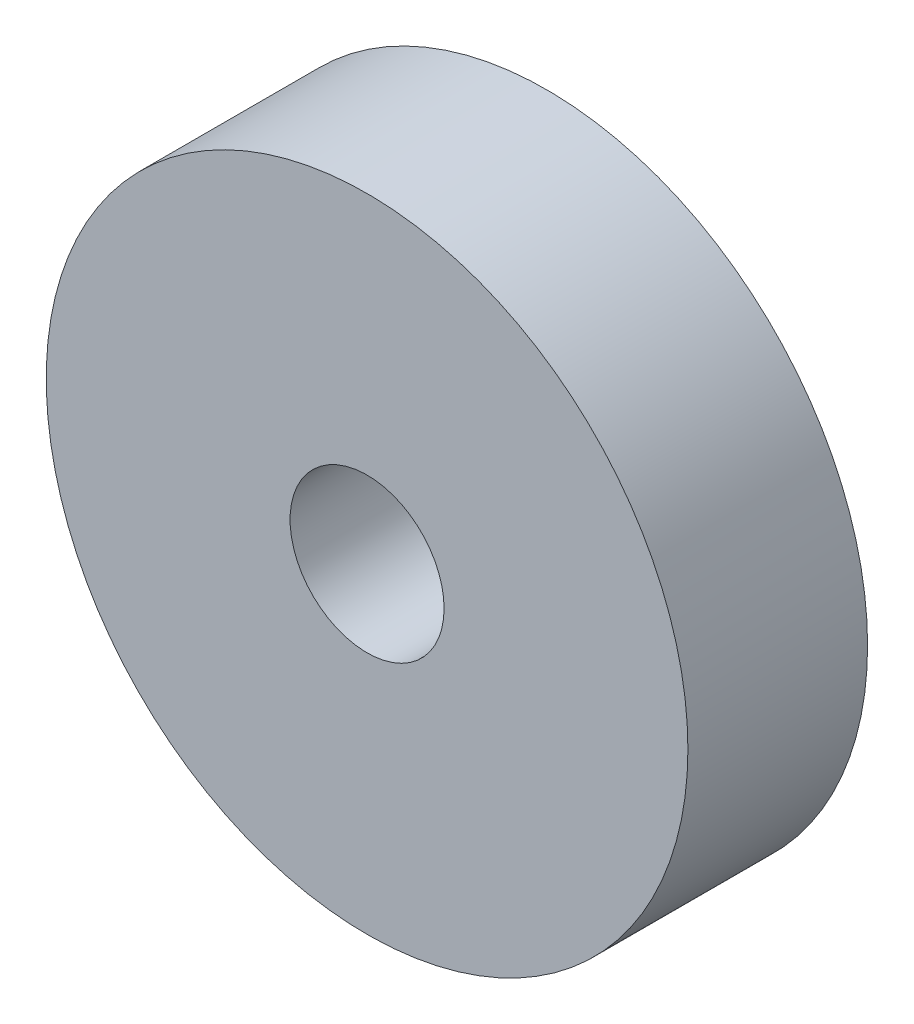
SolidWorks part; units mm, degrees
ref_plane "Front" through (0, 0, 0) normal (0, 0, 1) x (1, 0, 0)
ref_plane "Top" through (0, 0, 0) normal (0, 1, 0) x (1, 0, 0)
ref_plane "Right" through (0, 0, 0) normal (1, 0, 0) x (0, 0, -1)
sketch "Sketch2" plane through (0, 0, 0) normal (0, 0, 1) x (1, 0, 0)
  circle A0 centre (0, 0) radius 12.5
extrude "Boss-Extrude1" add sketch "Sketch2" along normal blind 7 contours A0
sketch "Sketch3" plane through (0, 0, 7) normal (0, 0, 1) x (1, 0, 0)
  circle A0 centre (0, 0) radius 3
extrude "Cut-Extrude1" cut sketch "Sketch3" against normal blind 7
